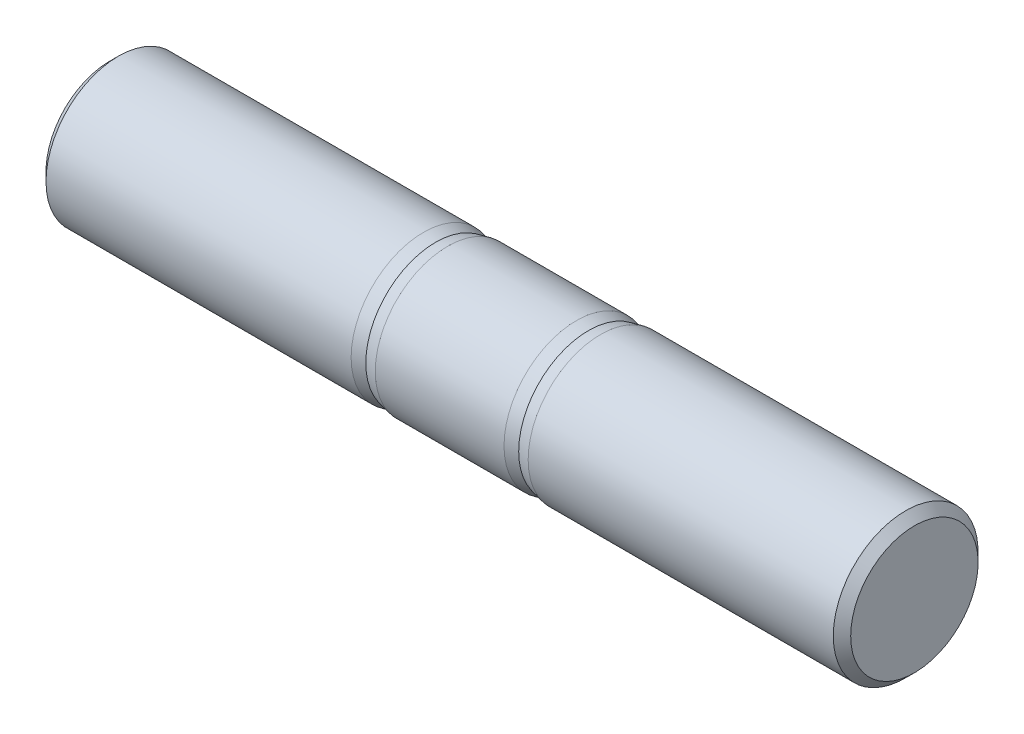
SolidWorks part; units mm, degrees
ref_plane "Front" through (0, 0, 0) normal (0, 0, 1) x (1, 0, 0)
ref_plane "Top" through (0, 0, 0) normal (0, 1, 0) x (1, 0, 0)
ref_plane "Right" through (0, 0, 0) normal (1, 0, 0) x (0, 0, -1)
sketch "Sketch1" plane through (0, 0, 0) normal (0, 0, 1) x (1, 0, 0)
  line L0 (-1.3108, 0) -> (30.3862, 0) construction
  line L1 (0, 0) -> (0, 18)
  line L2 (0, 18) -> (78, 18)
  line L3 (78, 18) -> (84, 16.701)
  line L4 (84, 16.701) -> (116, 16.701)
  line L5 (116, 16.701) -> (122, 18)
  line L6 (122, 18) -> (200, 18)
  line L7 (200, 18) -> (200, 0)
  line L8 (200, 0) -> (0, 0)
  dimension "X" = 6
  dimension "D2" = 6
  dimension "b" = 78
  dimension "d" = 36
  dimension "ds" = 33.402
  dimension "D1" = 78
  dimension "l" = 200
revolve "Base" add sketch "Sketch1" angle 360 about L0
cosmetic thread "ThreadCosmetic1" [suppressed] parameters "D1"=78, "D2"=31.67
cosmetic thread "ThreadCosmetic2" [suppressed] parameters "b"=78, "D2"=31.67
chamfer "HeadChamfer" distance 2.165 angle 45 2 edges at (0, 0, 18) (200, 0, 18)
sketch "Sketch4" plane through (0, 0, 0) normal (0, 0, 1) x (1, 0, 0)
  line L0 (78, 16.701) -> (84, 18)
  line L1 (78, 18) -> (78, -18) construction
  line L2 (84, 18) -> (116, 18)
  line L3 (116, 18) -> (122, 16.701)
  line L4 (122, 18) -> (122, -18) construction
  line L5 (122, 16.701) -> (78, 16.701)
  line L6 (-7.8091, 0) -> (106.8365, 0) construction
  line L8 (84, 33.6577) -> (84, 2.3423) construction
  line L10 (84, 16.701) -> (84, -16.701) construction
  line L11 (84, 16.701) -> (116, 16.701) construction
revolve "BaseBody" add sketch "Sketch4" angle 360 about L6
sketch "Sketch2" plane through (0, 0, 0) normal (0, 0, 1) x (1, 0, 0)
  line L0 (197.835, 16.1251) -> (198.9175, 18)
  line L1 (198.9175, 18) -> (198.9175, 18.5)
  line L2 (198.9175, 18.5) -> (196.7525, 18.5)
  line L3 (196.7525, 18.5) -> (196.7525, 18)
  line L4 (196.7525, 18) -> (197.835, 16.1251)
  line L5 (0, 0) -> (114.8799, 0) construction
  line L6 (197.835, 18) -> (197.835, -18) construction
  dimension "D1" = 60
  dimension "D2" = 60
  dimension "D3" = 0.5
  dimension "D4" = 2.165
  dimension "D5" = 36
revolve "Cut-Revolve10" [suppressed] cut sketch "Sketch2" angle 360 about L5
pattern_linear "LPattern10" [suppressed] count 30 spacing 2.598 along (1, 0, 0)
sketch "Sketch3" plane through (0, 0, 0) normal (0, 0, 1) x (1, 0, 0)
  line L0 (2.165, 16.1251) -> (3.2475, 18)
  line L1 (3.2475, 18) -> (3.2475, 18.5)
  line L2 (3.2475, 18.5) -> (1.0825, 18.5)
  line L3 (1.0825, 18.5) -> (1.0825, 18)
  line L4 (1.0825, 18) -> (2.165, 16.1251)
  line L5 (0, 0) -> (15.3216, 0) construction
  line L6 (0, 15.835) -> (0, -15.835) construction
  line L7 (2.165, 18) -> (2.165, -18) construction
  dimension "D1" = 60
  dimension "D2" = 60
  dimension "D3" = 36
  dimension "D4" = 0.5
  dimension "D5" = 2.165
revolve "Cut-Revolve11" [suppressed] cut sketch "Sketch3" angle 360 about L5
pattern_linear "LPattern11" [suppressed] count 30 spacing 2.598 along (1, 0, 0)
equation "\"D2@Sketch1\" = \"X@Sketch1\""
equation "\"D2@ThreadCosmetic2\" = \"D2@ThreadCosmetic1\""
equation "\"b@ThreadCosmetic2\" = \"b@Sketch1\""
equation "\"D1@HeadChamfer\" =  ( \"d@Sketch1\" - \"D2@ThreadCosmetic1\" )  / 2"
equation "\"D1@Sketch1\" = \"b@Sketch1\""
equation "\"D5@Sketch2\" = \"d@Sketch1\""
equation "\"D4@Sketch2\" =  ( \"d@Sketch1\" - \"D2@ThreadCosmetic2\" )  / 2"
equation "\"D3@LPattern10\" = \"D4@Sketch2\" * 1.2"
equation "\"D1@LPattern10\" = \"b@ThreadCosmetic2\" / \"D3@LPattern10\""
equation "\"D3@Sketch3\" = \"d@Sketch1\""
equation "\"D5@Sketch3\"  =  ( \"d@Sketch1\" - \"D2@ThreadCosmetic1\" )  / 2"
equation "\"D3@LPattern11\" = \"D5@Sketch3\" * 1.2"
equation "\"D1@LPattern11\" = \"D1@ThreadCosmetic1\" / \"D3@LPattern11\""
equation "\"D1@ThreadCosmetic1\" = \"b@Sketch1\""
